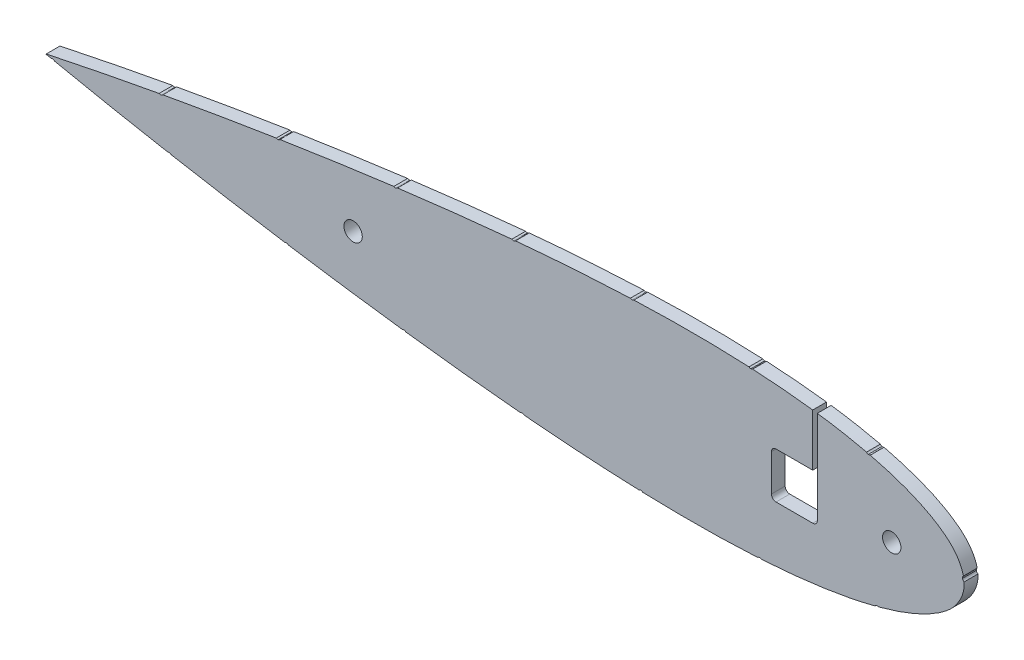
SolidWorks part; units mm, degrees
ref_plane "Front" through (0, 0, 0) normal (0, 0, 1) x (1, 0, 0)
ref_plane "Top" through (0, 0, 0) normal (0, 1, 0) x (1, 0, 0)
ref_plane "Right" through (0, 0, 0) normal (1, 0, 0) x (0, 0, -1)
sketch "Sketch1" plane through (0, 0, 0) normal (0, 0, 1) x (1, 0, 0)
  line L0 (0, 0) -> (-20, 0) construction
  line L1 (-200, -0.026) -> (-200, 0.026)
  line L4 (-32, -4) -> (-32, 4)
  line L5 (-33, 5) -> (-41, 5)
  line L6 (-42, 4) -> (-42, -4)
  line L7 (-41, -5) -> (-33, -5)
  line L8 (-32, -4) -> (-32, 4)
  line L9 (-33, 5) -> (-41, 5)
  line L10 (-42, 4) -> (-42, -4)
  line L11 (-41, -5) -> (-33, -5)
  circle A0 centre (-133.1086, 0) radius 2
  circle A1 centre (-15.7924, 0) radius 2
  arc A4 (-32, 4) -> (-33, 5) centre (-33, 4) ccw
  arc A5 (-41, 5) -> (-42, 4) centre (-41, 4) ccw
  arc A6 (-42, -4) -> (-41, -5) centre (-41, -4) ccw
  arc A7 (-33, -5) -> (-32, -4) centre (-33, -4) ccw
  arc A8 (-32, 4) -> (-33, 5) centre (-33, 4) ccw
  arc A9 (-41, 5) -> (-42, 4) centre (-41, 4) ccw
  arc A10 (-42, -4) -> (-41, -5) centre (-41, -4) ccw
  arc A11 (-33, -5) -> (-32, -4) centre (-33, -4) ccw
  spline S0 degree 3 poles (-1263.4129, 2779.3342) (-508.7656, -124.6898) (-351.618, -28.849) (-175.1972, 4.9535) (-158.6821, 7.8644) (-138.8483, 10.963) (-119.0176, 13.6524) (-99.1866, 15.8519) (-79.3508, 17.4108) (-62.8016, 17.9646) (-49.5701, 17.7436) (-39.6384, 17.1555) (-29.688, 16.02) (-21.4064, 14.4333) (-14.8011, 12.5462) (-9.7569, 10.6396) (-5.5318, 8.3438) (-1.6454, 5.1683) (1.0737, 0) (-1.6454, -5.1683) (-5.5318, -8.3438) (-9.7569, -10.6396) (-14.8011, -12.5462) (-21.4064, -14.4333) (-29.688, -16.02) (-39.6384, -17.1555) (-49.5701, -17.7436) (-62.8016, -17.9646) (-79.3508, -17.4108) (-99.1866, -15.8519) (-119.0176, -13.6524) (-138.8483, -10.963) (-158.6821, -7.8644) (-175.1972, -4.9535) (-351.6167, 28.8487) (-508.7632, 124.6883) (-1263.3951, -2779.2659) knots -1.211978 -1.211978 -1.211978 -1.211978 0.024604 0.049152 0.098109 0.146905 0.195555 0.244056 0.29241 0.340644 0.364754 0.388906 0.413178 0.437756 0.450305 0.46323 0.477068 0.485036 0.5 0.514964 0.522932 0.53677 0.549695 0.562244 0.586822 0.611094 0.635246 0.659356 0.70759 0.755944 0.804445 0.853095 0.901891 0.950848 0.975396 2.211969 2.211969 2.211969 2.211969 only from (-200, 0.026) to (-200, -0.026) construction
  spline S1 degree 3 poles (-200, 0.026) (-196.1337, 0.8245) (-188.9731, 2.314) (-175.1972, 4.9535) (-158.6821, 7.8644) (-138.8483, 10.963) (-119.0176, 13.6524) (-99.1866, 15.8519) (-79.3508, 17.4108) (-62.8016, 17.9646) (-49.5701, 17.7436) (-39.6384, 17.1555) (-29.688, 16.02) (-21.4064, 14.4333) (-14.8011, 12.5462) (-9.7569, 10.6396) (-5.5318, 8.3438) (-1.6454, 5.1683) (1.0737, 0) (-1.6454, -5.1683) (-5.5318, -8.3438) (-9.7569, -10.6396) (-14.8011, -12.5462) (-21.4064, -14.4333) (-29.688, -16.02) (-39.6384, -17.1555) (-49.5701, -17.7436) (-62.8016, -17.9646) (-79.3508, -17.4108) (-99.1866, -15.8519) (-119.0176, -13.6524) (-138.8483, -10.963) (-158.6821, -7.8644) (-175.1972, -4.9535) (-188.9731, -2.314) (-196.1337, -0.8245) (-200, -0.026) knots -0.00419 -0.00419 -0.00419 -0.00419 0.024604 0.049152 0.098109 0.146905 0.195555 0.244056 0.29241 0.340644 0.364754 0.388906 0.413178 0.437756 0.450305 0.46323 0.477068 0.485036 0.5 0.514964 0.522932 0.53677 0.549695 0.562244 0.586822 0.611094 0.635246 0.659356 0.70759 0.755944 0.804445 0.853095 0.901891 0.950848 0.975396 1.00419 1.00419 1.00419 1.00419
  point P21 (-42, 0)
  dimension "D2" = 4
  dimension "D1" = 0
extrude "Boss-Extrude1" add sketch "Sketch1" along normal blind 3
sketch "Sketch2" plane through (0, 0, 3) normal (0, 0, 1) x (1, 0, 0)
  line L0 (-32, -4) -> (-32, 4) construction
  line L1 (-33, 2.3323) -> (-32, 2.3323)
  line L2 (-33, 2.3323) -> (-33, 20.311)
  line L3 (-33, 20.311) -> (-32, 20.311)
  line L4 (-32, 2.3323) -> (-32, 20.311)
  text T0 ". . . . . . . . . . . . . . . . ." font "Century Gothic" height in points 28
  dimension "D1" = 1
extrude "Cut-Extrude1" cut sketch "Sketch2" against normal blind 10
sketch "Sketch3" plane through (0, 0, 3) normal (0, 0, 1) x (1, 0, 0)
  line L1 (-210, 24.974) -> (7.307, 24.974)
  line L2 (-210, 24.974) -> (-210, -25.026)
  line L3 (-210, -25.026) -> (7.307, -25.026)
  line L4 (7.307, 24.974) -> (7.307, -25.026)
  point P4 (-210, -0.026)
  point P6 (7.307, 24.974)
  dimension "D1" = 10
  dimension "D2" = 50
